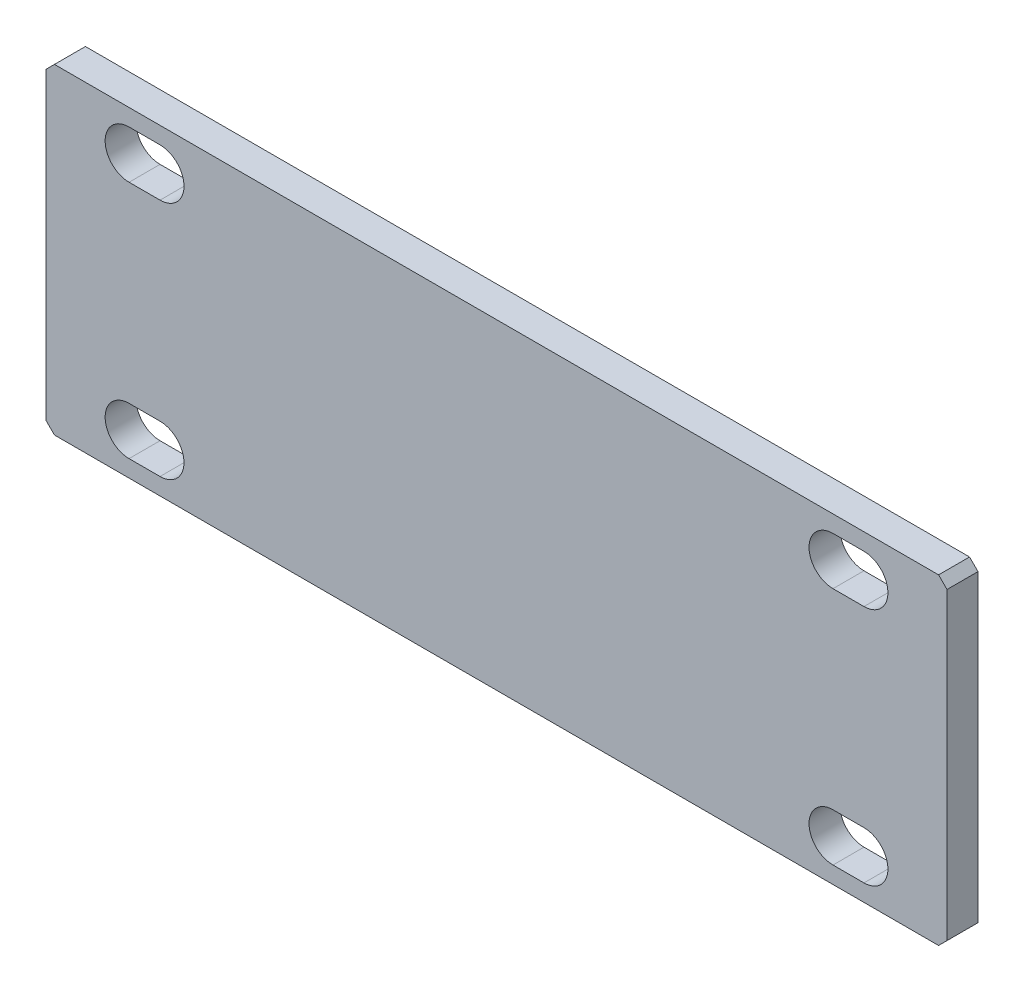
SolidWorks part; units mm, degrees
ref_plane "前视基准面" through (0, 0, 0) normal (0, 0, 1) x (1, 0, 0)
ref_plane "上视基准面" through (0, 0, 0) normal (0, 1, 0) x (1, 0, 0)
ref_plane "右视基准面" through (0, 0, 0) normal (1, 0, 0) x (0, 0, -1)
other "Configuration Table"
sketch "Four 3.4 mm power PCB slots - nominal pattern 50 x 17 profile" plane through (0, 0, 0) normal (0, 0, 1) x (1, 0, 0)
  line L0 (-31.4, -11.4) -> (31.4, -11.4)
  line L1 (31.4, -11.4) -> (32, -10.8)
  line L2 (32, -10.8) -> (32, 10.8)
  line L3 (32, 10.8) -> (31.4, 11.4)
  line L4 (31.4, 11.4) -> (-31.4, 11.4)
  line L5 (-31.4, 11.4) -> (-32, 10.8)
  line L6 (-32, 10.8) -> (-32, -10.8)
  line L7 (-32, -10.8) -> (-31.4, -11.4)
  line L8 (-26.1, -10.2) -> (-23.9, -10.2)
  line L9 (-23.9, -6.8) -> (-26.1, -6.8)
  line L10 (-26.1, 6.8) -> (-23.9, 6.8)
  line L11 (-23.9, 10.2) -> (-26.1, 10.2)
  line L12 (23.9, -10.2) -> (26.1, -10.2)
  line L13 (26.1, -6.8) -> (23.9, -6.8)
  line L14 (23.9, 6.8) -> (26.1, 6.8)
  line L15 (26.1, 10.2) -> (23.9, 10.2)
  arc A0 (-23.9, -10.2) -> (-23.9, -6.8) centre (-23.9, -8.5) ccw
  arc A1 (-26.1, -6.8) -> (-26.1, -10.2) centre (-26.1, -8.5) ccw
  arc A2 (-23.9, 6.8) -> (-23.9, 10.2) centre (-23.9, 8.5) ccw
  arc A3 (-26.1, 10.2) -> (-26.1, 6.8) centre (-26.1, 8.5) ccw
  arc A4 (26.1, -10.2) -> (26.1, -6.8) centre (26.1, -8.5) ccw
  arc A5 (23.9, -6.8) -> (23.9, -10.2) centre (23.9, -8.5) ccw
  arc A6 (26.1, 6.8) -> (26.1, 10.2) centre (26.1, 8.5) ccw
  arc A7 (23.9, 10.2) -> (23.9, 6.8) centre (23.9, 8.5) ccw
extrude "Four 3.4 mm power PCB slots - nominal pattern 50 x 17" add sketch "Four 3.4 mm power PCB slots - nominal pattern 50 x 17 profile" along normal blind 2.2
